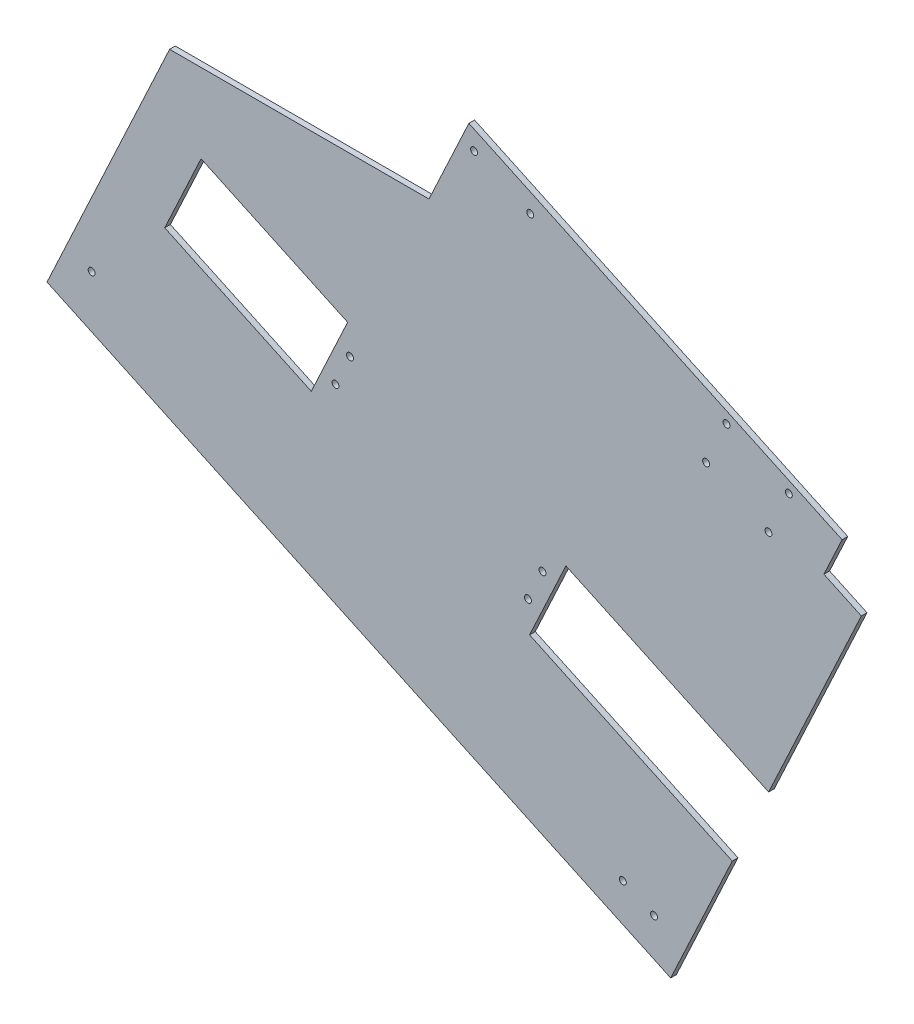
SolidWorks part; units mm, degrees
material "Balsa"
ref_plane "Front Plane" through (0, 0, 0) normal (0, 0, 1) x (1, 0, 0)
ref_plane "Top Plane" through (0, 0, 0) normal (0, 1, 0) x (1, 0, 0)
ref_plane "Right Plane" through (0, 0, 0) normal (1, 0, 0) x (0, 0, -1)
sketch "Sketch1" plane through (0, 0, 0) normal (0, 0, 1) x (1, 0, 0)
  line L0 (-261.1014, 0.0035) -> (-110.3324, 0.0035)
  line L1 (-110.3324, 0.0035) -> (-87.1479, 49.7228)
  line L2 (-87.1479, 49.7228) -> (129.7831, -51.4338)
  line L3 (129.7831, -51.4338) -> (119.2177, -74.0915)
  line L4 (119.2177, -74.0915) -> (140.969, -84.2344)
  line L5 (140.969, -84.2344) -> (30.1585, -321.8683)
  line L6 (30.1585, -321.8683) -> (-332.3646, -152.8209)
  line L7 (-332.3646, -152.8209) -> (-261.1014, 0.0035)
  line L8 (-257.4117, 0.0035) -> (-57.4117, 0.0035) construction
  line L9 (-332.3646, -152.8209) -> (-261.0998, 0.0069) construction
  line L10 (30.1585, -321.8683) -> (-332.3646, -152.8209) construction
  line L11 (140.969, -84.2344) -> (30.1585, -321.8683) construction
  line L12 (-189.2372, 97.3278) -> (129.7831, -51.4338) construction
  line L13 (119.2177, -74.0915) -> (140.969, -84.2344) construction
  line L14 (129.7831, -51.4338) -> (119.2177, -74.0915) construction
  line L15 (-110.3324, 0.0035) -> (-87.1479, 49.7228) construction
  circle A0 centre (87.0035, -69.0002) radius 2
  circle A1 centre (98.8369, -43.6236) radius 2
  circle A2 centre (62.5845, -26.7189) radius 2
  circle A3 centre (50.7512, -52.0955) radius 2
  circle A4 centre (2.3586, -286.8374) radius 2
  circle A5 centre (-306.4229, -134.5749) radius 2
  circle A6 centre (20.4847, -295.2897) radius 2
  circle A7 centre (2.3586, -286.8374) radius 2 construction
  circle A8 centre (20.4847, -295.2897) radius 2 construction
  dimension "D1" = 4
  dimension "D2" = 4
  dimension "D3" = 4
  dimension "D4" = 4
  dimension "D7" = 4
  dimension "D5" = 27.5
  dimension "D6" = 15.8
extrude "Boss-Extrude1" add sketch "Sketch1" along normal up to surface (3.3 mm away)
sketch "Sketch2" plane through (0, 0, 0) normal (0, 0, -1) x (-1, 0, 0)
  line L0 (87.1479, 49.7228) -> (110.3324, 0.0035) construction
  line L1 (-129.7831, -51.4338) -> (87.1479, 49.7228) construction
  circle A0 centre (51.4966, 22.0645) radius 2
  circle A1 centre (84.1237, 37.2788) radius 2
  dimension "D1" = 4
  dimension "D2" = 4
  dimension "D3" = 8
  dimension "D4" = 36
  dimension "D5" = 10
  dimension "D6" = 10
extrude "Cut-Extrude1" cut sketch "Sketch2" against normal through all
sketch "Sketch5" plane through (0, 0, 3.3) normal (0, 0, 1) x (1, 0, 0)
  line L0 (65.9543, -245.104) -> (-51.8657, -190.1636)
  line L1 (140.969, -84.2344) -> (30.1585, -321.8683) construction
  line L2 (-51.8657, -190.1636) -> (-30.7348, -144.8482)
  line L3 (-30.7348, -144.8482) -> (87.0852, -199.7886)
  line L4 (87.0852, -199.7886) -> (65.9543, -245.104)
  line L5 (119.2177, -74.0915) -> (140.969, -84.2344) construction
  dimension "D1" = 130
  dimension "D2" = 127.5
  dimension "D3" = 50
extrude "Cut-Extrude2" cut sketch "Sketch5" against normal blind 10
sketch "Sketch6" plane through (0, 0, 3.3) normal (0, 0, 1) x (1, 0, 0)
  line L0 (-178.7488, -130.9971) -> (-157.6179, -85.6817)
  line L1 (-157.6179, -85.6817) -> (-242.8108, -45.9555)
  line L2 (-242.8108, -45.9555) -> (-263.9417, -91.2709)
  line L3 (-263.9417, -91.2709) -> (-178.7488, -130.9971)
  line L5 (87.0852, -199.7886) -> (-30.7348, -144.8482) construction
  line L6 (-51.8657, -190.1636) -> (65.9543, -245.104) construction
  line L7 (-332.3646, -152.8209) -> (-261.1014, 0.0035) construction
  line L8 (129.7831, -51.4338) -> (119.2177, -74.0915) construction
  dimension "D1" = 130
  dimension "D2" = 340
extrude "Cut-Extrude3" cut sketch "Sketch6" against normal blind 10
sketch "Sketch7" plane through (0, 0, 3.3) normal (0, 0, 1) x (1, 0, 0)
  circle A0 centre (-52.7985, -172.5711) radius 2
  circle A1 centre (-44.3462, -154.4449) radius 2
  circle A2 centre (-164.6725, -120.4034) radius 2
  circle A3 centre (-156.2202, -102.2772) radius 2
  circle A4 centre (-52.7985, -172.5711) radius 2 construction
  circle A5 centre (-44.3462, -154.4449) radius 2 construction
  circle A6 centre (-164.6725, -120.4034) radius 2 construction
  circle A7 centre (-156.2202, -102.2772) radius 2 construction
extrude "Cut-Extrude4" cut sketch "Sketch7" against normal blind 10
